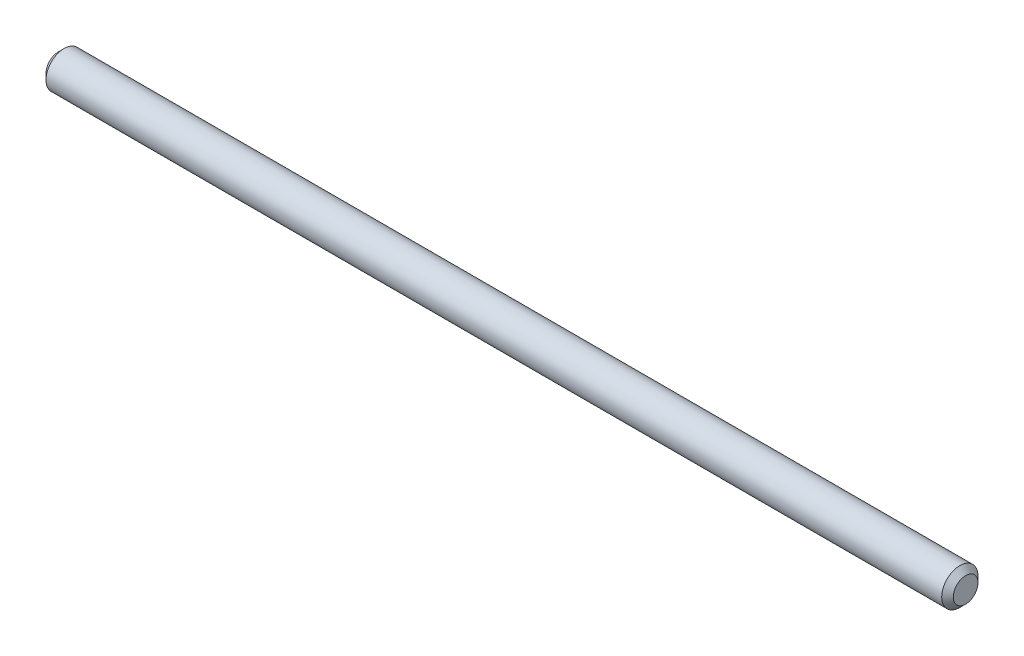
SolidWorks part; units mm, degrees
ref_plane "Plan de face" through (0, 0, 0) normal (0, 0, 1) x (1, 0, 0)
ref_plane "Plan de dessus" through (0, 0, 0) normal (0, 1, 0) x (1, 0, 0)
ref_plane "Plan de droite" through (0, 0, 0) normal (1, 0, 0) x (0, 0, -1)
ref_plane "Plan1" through (0, 0, 0) normal (0, 0, -1) x (-1, 0, 0)
sketch "Esquisse1" plane through (0, 0, 0) normal (0, 0, -1) x (-1, 0, 0)
  line L0 (-200, 2.7272) -> (-200, 0)
  line L1 (-200, 0) -> (0, 0)
  line L2 (0, 0) -> (0, 2.7272)
  line L3 (0, 2.7272) -> (-1.2728, 4)
  line L4 (-1.2728, 4) -> (-198.7272, 4)
  line L5 (-198.7272, 4) -> (-200, 2.7272)
  line L6 (-200, 0) -> (0, 0) construction
revolve "Révolution1" add sketch "Esquisse1" angle 360 about L6
